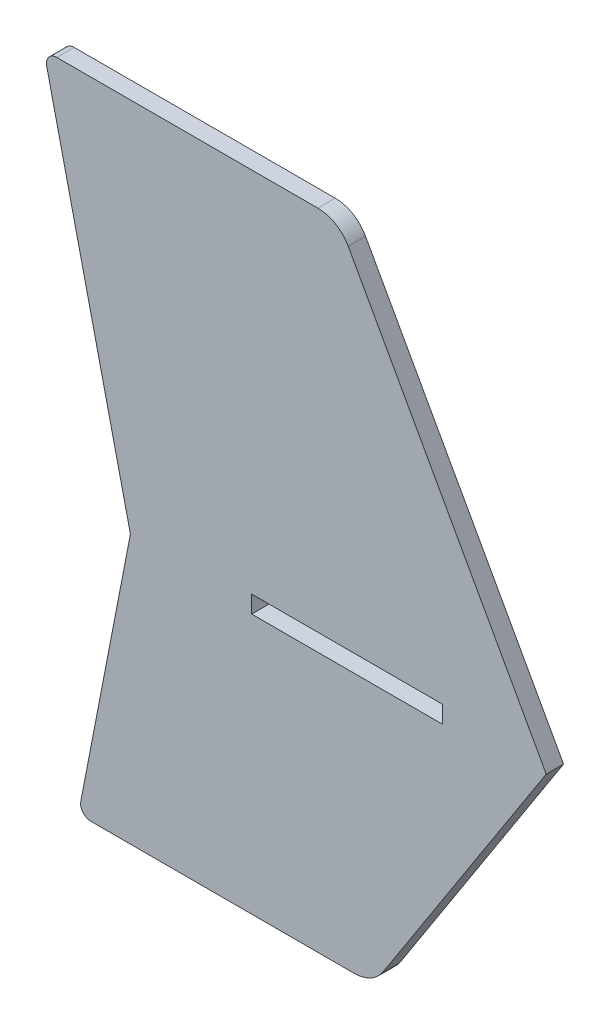
SolidWorks part; units mm, degrees
ref_plane "Ebene vorne" through (0, 0, 0) normal (0, 0, 1) x (1, 0, 0)
ref_plane "Ebene oben" through (0, 0, 0) normal (0, 1, 0) x (1, 0, 0)
ref_plane "Ebene rechts" through (0, 0, 0) normal (1, 0, 0) x (0, 0, -1)
sketch "Skizze1" plane through (0, 0, 0) normal (0, 0, 1) x (1, 0, 0)
  line L1 (-50, 186) -> (35, 186)
  line L2 (35, 186) -> (95, 77.5)
  line L3 (95, 77.5) -> (45, 0)
  line L4 (45, 0) -> (0, 0)
  line L5 (-50, 186) -> (-25, 77.5)
  line L6 (-25, 77.5) -> (-40, 0)
  line L7 (-40, 0) -> (0, 0)
  dimension "D1" = 186
  dimension "D2" = 85
  dimension "50" = 50
  dimension "D4" = 60
  dimension "D5" = 77.5
  dimension "D6" = 45
  dimension "D7" = 40
  dimension "D8" = 120
extrude "Grundplatte" add sketch "Skizze1" along normal blind 5 contours L1 L2 L3 L4 L7 L6 L5
sketch "Skizze2" plane through (0, 0, 5) normal (0, 0, 1) x (1, 0, 0)
  line L1 (10, 75) -> (65, 75)
  line L2 (10, 75) -> (10, 80)
  line L3 (10, 80) -> (65, 80)
  line L4 (65, 75) -> (65, 80)
  line L5 (65, 77.5) -> (95, 77.5) construction
  dimension "D1" = 55
  dimension "D2" = 5
  dimension "D3" = 30
extrude "NutHöhenleitwerk" cut sketch "Skizze2" against normal blind 15
fillet "Verrundung1" radius 10 2 edges at (45, 0, 2.5) (35, 186, 2.5)
fillet "Verrundung2" radius 3 2 edges at (-40, 0, 2.5) (-50, 186, 2.5)
